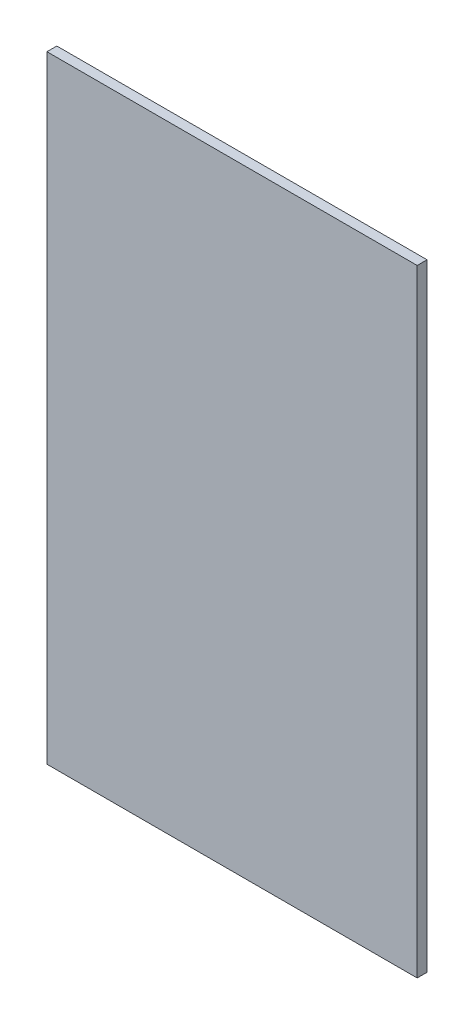
SolidWorks part; units mm, degrees
ref_plane "Front Plane" through (0, 0, 0) normal (0, 0, 1) x (1, 0, 0)
ref_plane "Top Plane" through (0, 0, 0) normal (0, 1, 0) x (1, 0, 0)
ref_plane "Right Plane" through (0, 0, 0) normal (1, 0, 0) x (0, 0, -1)
sketch "Sketch1" plane through (0, 0, 0) normal (0, 0, 1) x (1, 0, 0)
  line L1 (-1.5, -2.5) -> (1.5, -2.5)
  line L2 (-1.5, -2.5) -> (-1.5, 2.5)
  line L3 (-1.5, 2.5) -> (1.5, 2.5)
  line L4 (1.5, -2.5) -> (1.5, 2.5)
  line L5 (-1.5, -2.5) -> (1.5, 2.5) construction
  line L6 (-1.5, 2.5) -> (1.5, -2.5) construction
  point P0 (0, 0)
  dimension "D1" = 3
  dimension "D2" = 5
extrude "Boss-Extrude1" add sketch "Sketch1" along normal blind 0.08
